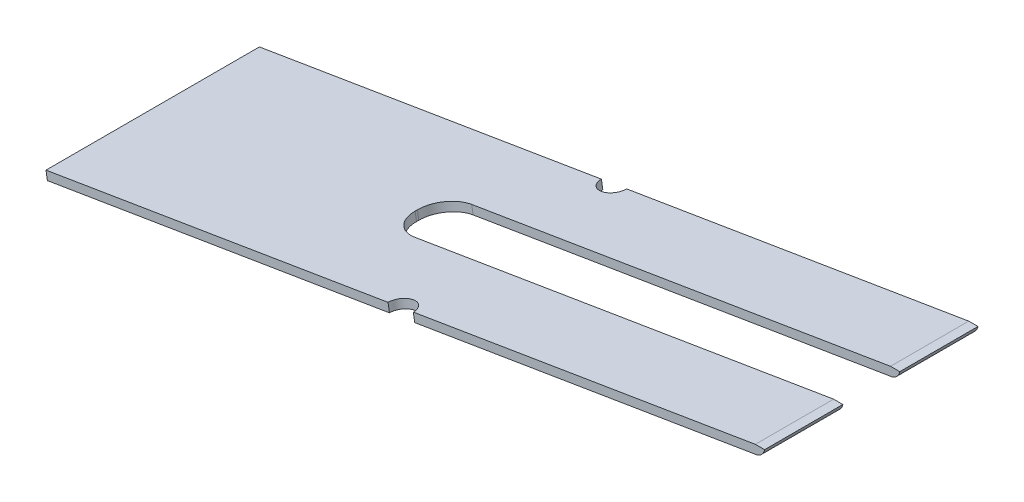
SolidWorks part; units mm, degrees
ref_plane "Alzado" through (0, 0, 0) normal (0, 0, 1) x (1, 0, 0)
ref_plane "Planta" through (0, 0, 0) normal (0, 1, 0) x (1, 0, 0)
ref_plane "Vista lateral" through (0, 0, 0) normal (1, 0, 0) x (0, 0, -1)
sketch "Croquis1" plane through (0, 0, 0) normal (0, 0, 1) x (1, 0, 0)
  line L1 (6.1373, -15.5501) -> (-6.5627, -15.5501) construction
  line L2 (4.5373, -15.5501) -> (-7.9293, -17.6098)
  line L3 (-7.9293, -17.6098) -> (-7.9048, -17.7578)
  line L5 (4.5617, -15.6981) -> (-7.9048, -17.7578)
  line L6 (4.5373, -15.5501) -> (4.6999, -15.5501)
  line L7 (4.6999, -15.5501) -> (4.5373, -15.5501) construction
  arc A0 (4.5617, -15.6981) -> (4.6999, -15.5501) centre (4.5107, -15.5119) ccw
  dimension "D2" = 0.15
  dimension "D3" = 0.15
extrude "Saliente-Extruir1" add sketch "Croquis1" along normal mid plane 3.75
sketch "Croquis2" plane through (2.646, -16.0146, 0) normal (0.163, -0.9866, 0) x (0.9866, 0.163, 0)
  line L0 (1.9417, 1.875) -> (1.9417, -1.875) construction
  line L1 (9.8817, -0.5) -> (-5.5183, -0.5)
  line L2 (9.8817, -0.5) -> (9.8817, 0.5)
  line L3 (9.8817, 0.5) -> (-5.5183, 0.5)
  line L4 (-5.9983, -0.02) -> (-5.9983, 0.02)
  line L5 (9.8817, -0.5) -> (-5.9983, 0.5) construction
  line L6 (9.8817, 0.5) -> (-5.9983, -0.5) construction
  line L7 (-10.6938, 1.875) -> (1.9417, 1.875) construction
  line L8 (-10.6938, -1.875) -> (1.9417, -1.875) construction
  circle A0 centre (-4.376, 1.875) radius 0.225
  circle A1 centre (-4.376, -1.875) radius 0.225
  arc A2 (-5.9983, -0.02) -> (-5.5183, -0.5) centre (-5.5183, -0.02) ccw
  arc A3 (-5.9983, 0.02) -> (-5.5183, 0.5) centre (-5.5183, 0.02) cw
  point P0 (1.9417, 0)
  dimension "D1" = 0.45
  dimension "D2" = 0.48
  dimension "D3" = 1
  dimension "D4" = 15.4
extrude "Cortar-Extruir1" cut sketch "Croquis2" against normal blind 0.3
